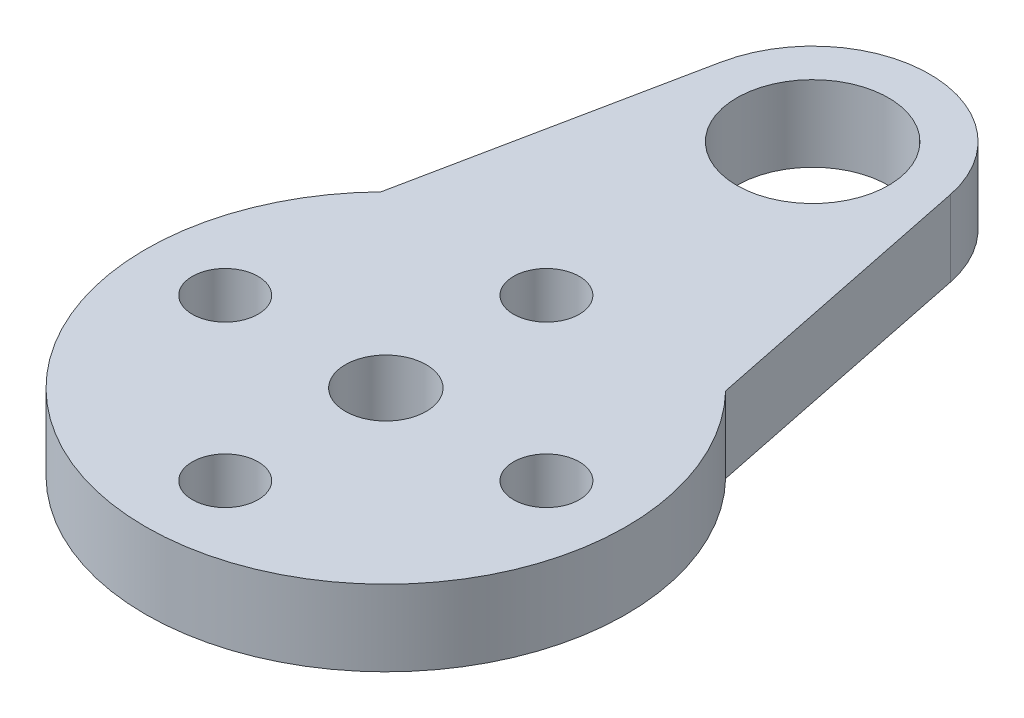
SolidWorks part; units mm, degrees
ref_plane "Front Plane" through (0, 0, 0) normal (0, 0, 1) x (1, 0, 0)
ref_plane "Top Plane" through (0, 0, 0) normal (0, 1, 0) x (1, 0, 0)
ref_plane "Right Plane" through (0, 0, 0) normal (1, 0, 0) x (0, 0, -1)
sketch "Sketch1" plane through (0, 0, 0) normal (0, 1, 0) x (1, 0, 0)
  line L1 (-4.5316, 17.7996) -> (-7.8384, 1.6)
  line L2 (4.5316, 17.7996) -> (7.8384, 1.6)
  arc A0 (-7.8384, 1.6) -> (7.8384, 1.6) centre (0, 0) ccw
  arc A1 (4.5316, 17.7996) -> (-4.5316, 17.7996) centre (0, 16.8746) ccw
  circle A2 centre (0, 16.8746) radius 3
  circle A3 centre (0, 0) radius 1.6
extrude "Boss-Extrude1" add sketch "Sketch1" along normal blind 3
sketch "Sketch2" plane through (0, 3, 0) normal (0, 1, 0) x (1, 0, 0)
  line L0 (0, 0) -> (0, 6.35) construction
  circle A0 centre (0, 6.35) radius 1.3
  circle A1 centre (6.35, 0) radius 1.3
  circle A2 centre (0, -6.35) radius 1.3
  circle A3 centre (-6.35, 0) radius 1.3
  point P13 (0, 0)
  dimension "D1" = 4
extrude "Cut-Extrude1" cut sketch "Sketch2" against normal blind 3
sketch "Sketch3" plane through (0, 3, 0) normal (0, 1, 0) x (1, 0, 0)
  line L0 (-7.8384, 1.6) -> (-6.8137, 6.62)
  line L1 (6.8137, 6.62) -> (7.8384, 1.6)
  line L2 (7.8384, 1.6) -> (4.5316, 17.7996) construction
  arc A1 (-6.8137, 6.62) -> (6.8137, 6.62) centre (0, 0) ccw
  arc A2 (-7.8384, 1.6) -> (7.8384, 1.6) centre (0, 0) ccw construction
  arc A3 (-7.8384, 1.6) -> (7.8384, 1.6) centre (0, 0) ccw
extrude "Boss-Extrude2" add sketch "Sketch3" against normal blind 3
